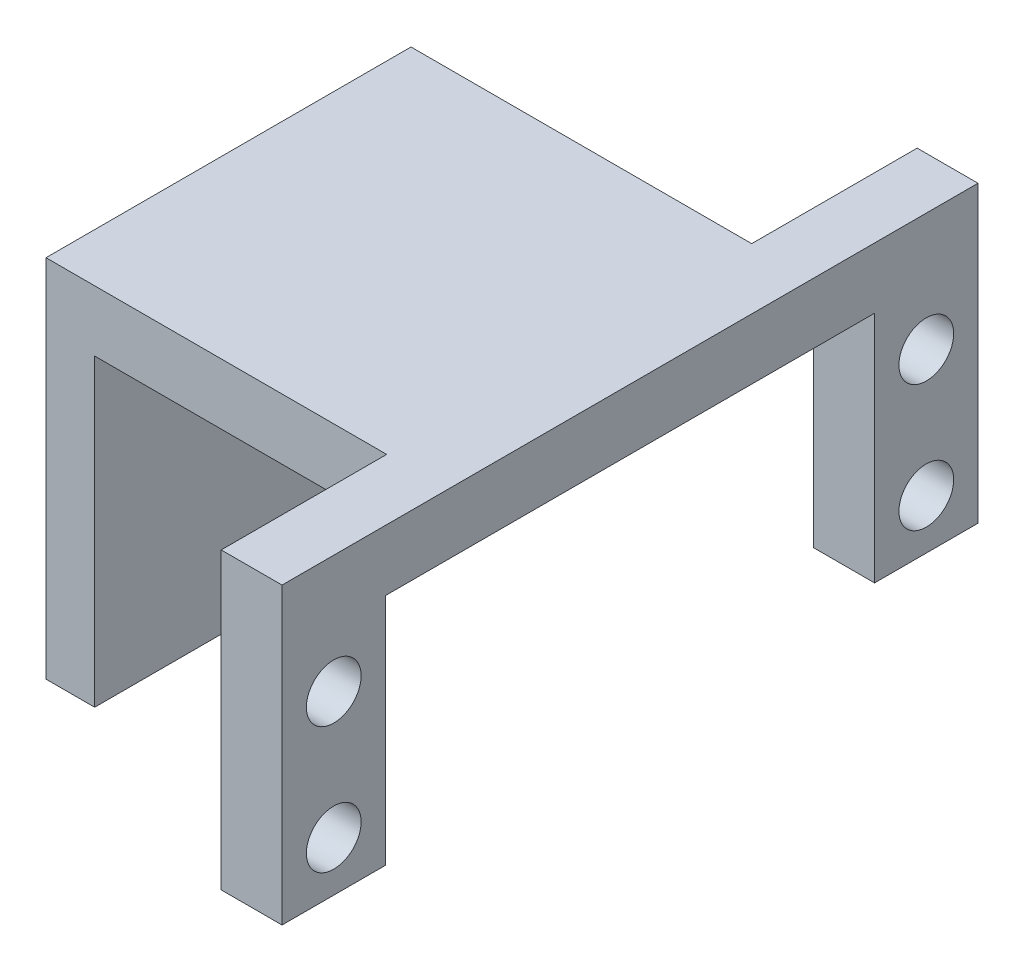
SolidWorks part; units mm, degrees
ref_plane "Front Plane" through (0, 0, 0) normal (0, 0, 1) x (1, 0, 0)
ref_plane "Top Plane" through (0, 0, 0) normal (0, 1, 0) x (1, 0, 0)
ref_plane "Right Plane" through (0, 0, 0) normal (1, 0, 0) x (0, 0, -1)
sketch "Sketch1" plane through (0, 0, 0) normal (1, 0, 0) x (0, 0, -1)
  line L1 (0, 0) -> (30, 0)
  line L2 (0, 0) -> (0, 30)
  line L3 (0, 30) -> (30, 30)
  line L4 (30, 0) -> (30, 30)
  dimension "D1" = 30
  dimension "D2" = 30
extrude "Boss-Extrude1" add sketch "Sketch1" along normal blind 4
sketch "Sketch3" plane through (4, 0, 0) normal (1, 0, 0) x (0, 0, -1)
  line L0 (30, 0) -> (30, 30) construction
  line L1 (0, 30) -> (30, 30)
  line L2 (0, 30) -> (0, 25)
  line L3 (0, 25) -> (30, 25)
  line L4 (30, 30) -> (30, 25)
  dimension "D1" = 5
extrude "Boss-Extrude2" add sketch "Sketch3" along normal blind 24
sketch "Sketch4" plane through (28, 0, 0) normal (1, 0, 0) x (0, 0, -1)
  line L0 (0, 30) -> (0, 25) construction
  line L1 (-5.1, 30) -> (35.1, 30)
  line L2 (-5.1, 30) -> (-5.1, 25)
  line L3 (-5.1, 25) -> (35.1, 25)
  line L4 (35.1, 30) -> (35.1, 25)
  line L5 (30, 25) -> (30, 30) construction
  line L6 (30, 30) -> (0, 30) construction
  line L7 (0, 25) -> (30, 25) construction
  dimension "D1" = 5.1
  dimension "D2" = 5.1
  dimension "D3" = 0
  dimension "D4" = 0
extrude "Boss-Extrude3" add sketch "Sketch4" along normal blind 5
sketch "Sketch5" plane through (0, 0, 5.1) normal (0, 0, 1) x (1, 0, 0)
  line L0 (28, 30) -> (28, 25) construction
  line L1 (33, 30) -> (28, 30)
  line L2 (33, 30) -> (33, 5.8)
  line L3 (33, 5.8) -> (28, 5.8)
  line L4 (28, 30) -> (28, 5.8)
  line L5 (33, 25) -> (28, 25) construction
  dimension "D1" = 0
  dimension "D2" = 19.2
extrude "Boss-Extrude4" add sketch "Sketch5" along normal blind 8.5
pattern_linear "LPattern1" count 2 spacing 48.7 along (0, 0, -1) of "Boss-Extrude4"
hole_wizard "M4 Clearance Hole1" positions "Sketch6" profile "Sketch7" hole size "M4" standard "ANSI Metric" end condition up to next
sketch "Sketch6" plane through (33, 0, 0) normal (1, 0, 0) x (0, 0, -1)
  line L0 (-5.1, 25) -> (35.1, 25) construction
  line L2 (-5.1, 5.8) -> (-5.1, 25) construction
  line L5 (35.1, 5.8) -> (35.1, 25) construction
  point P0 (-9.35, 20.3)
  point P2 (-9.35, 9.9)
  point P4 (39.35, 20.3)
  point P6 (39.35, 9.9)
  point P19 (0, 0)
  dimension "D1" = 4.7
  dimension "D2" = 10.4
  dimension "D3" = 0
  dimension "D4" = 0
  dimension "D5" = 0
  dimension "D6" = 4.25
  dimension "D7" = 4.25
sketch "Sketch7" plane through (33, 20.3, 9.35) normal (0, 1, 0) x (0, 0, -1)
  line L0 (0, 0) -> (0, 5)
  line L1 (0, 5) -> (2.25, 5)
  line L2 (2.25, 5) -> (2.25, 0)
  line L5 (2.25, 0) -> (0, 0)
  line L11 (0, -6.35) -> (0, 107.95) construction
  dimension "Thru Hole Dia." = 4.5
  dimension "Thru Hole Depth" = 5
